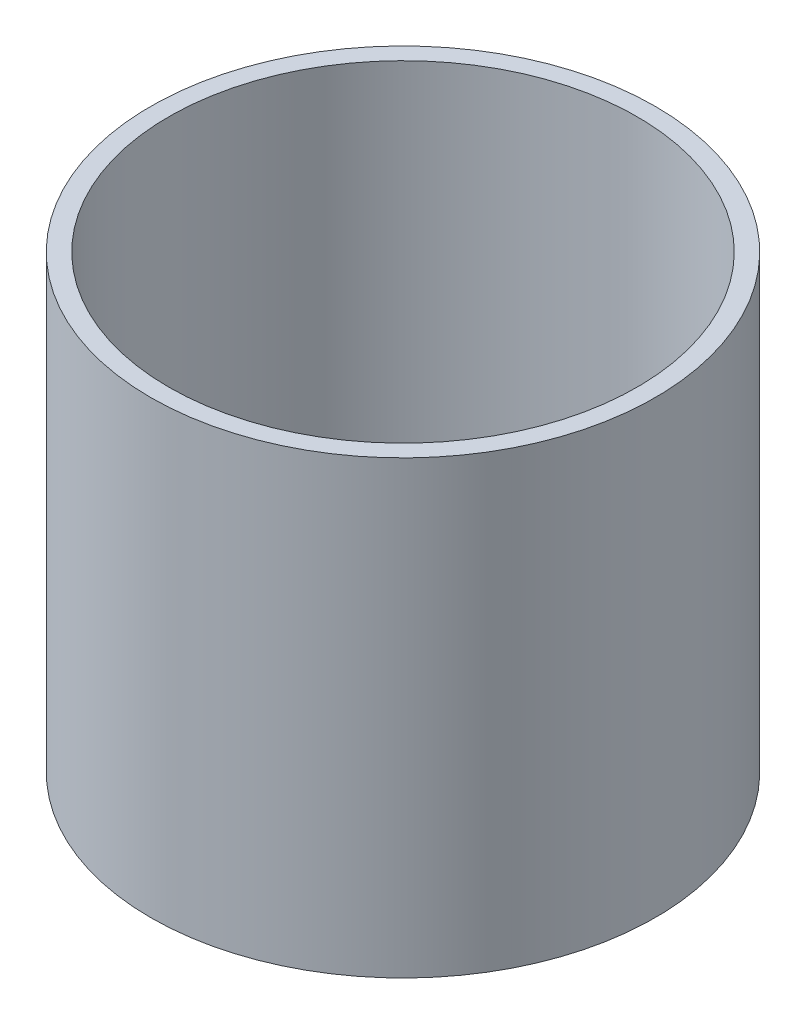
SolidWorks part; units mm, degrees
ref_plane "Front Plane" through (0, 0, 0) normal (0, 0, 1) x (1, 0, 0)
ref_plane "Top Plane" through (0, 0, 0) normal (0, 1, 0) x (1, 0, 0)
ref_plane "Right Plane" through (0, 0, 0) normal (1, 0, 0) x (0, 0, -1)
sketch "Sketch1" plane through (0, 0, 0) normal (0, 1, 0) x (1, 0, 0)
  circle A1 centre (0, 0) radius 13
  circle A2 centre (0, 0) radius 14
  dimension "D1" = 26
  dimension "D2" = 1
extrude "Boss-Extrude1" add sketch "Sketch1" along normal blind 25
